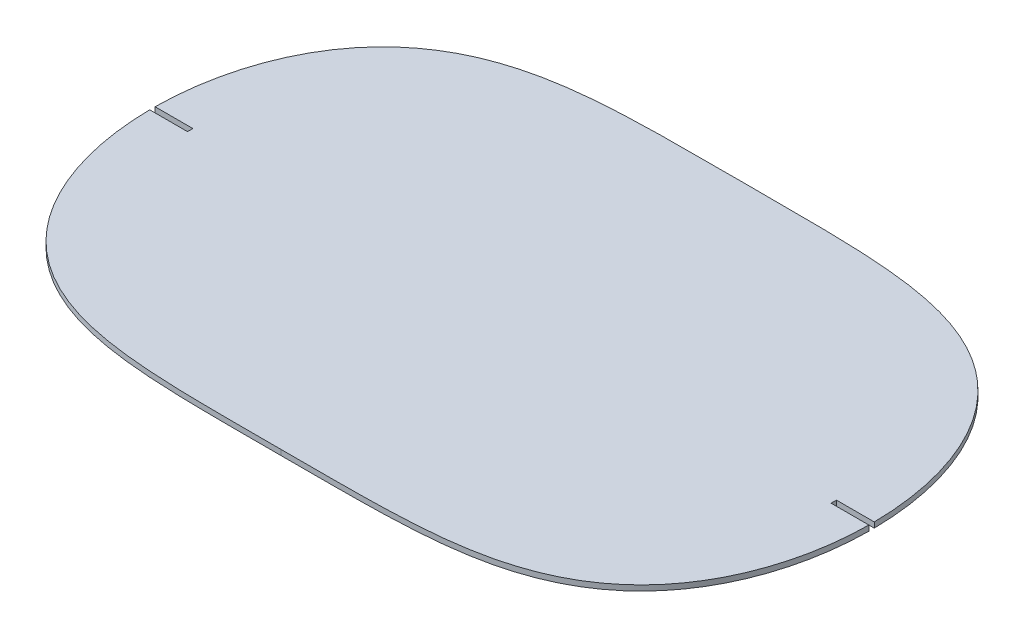
SolidWorks part; units mm, degrees
ref_plane "Front Plane" through (0, 0, 0) normal (0, 0, 1) x (1, 0, 0)
ref_plane "Top Plane" through (0, 0, 0) normal (0, 1, 0) x (1, 0, 0)
ref_plane "Right Plane" through (0, 0, 0) normal (1, 0, 0) x (0, 0, -1)
sketch "Sketch1" plane through (0, 0, 0) normal (0, 1, 0) x (1, 0, 0)
  spline S0 degree 4 poles (0, 129.0994) (4.3298, 129.0999) (12.9895, 129.0995) (25.9763, 129.0992) (43.2902, 129.014) (60.6007, 128.6712) (77.8947, 127.8129) (95.543, 126.046) (113.014, 122.896) (130.0464, 117.7971) (146.1581, 110.2269) (160.4313, 100.265) (172.6933, 87.9119) (182.6634, 73.6634) (190.3404, 58.0791) (195.8654, 41.6227) (199.4008, 24.6362) (201.0699, 7.3707) (200.9352, -9.9735) (198.9912, -27.2107) (195.1663, -44.1354) (189.3287, -60.4854) (181.3147, -75.9018) (170.9944, -89.9023) (157.8662, -102.4377) (141.9679, -112.6829) (124.642, -119.7567) (106.7084, -124.2192) (88.4462, -126.9034) (70.0513, -128.3227) (45.6298, -129.0998) (25.3491, -129.0993) (10.1399, -129.0994) (0, -129.0994) knots 0 0 0 0 0 0.03122 0.06244 0.093642 0.124843 0.156053 0.187263 0.221451 0.252662 0.283872 0.315082 0.346292 0.377502 0.408713 0.439923 0.471133 0.502344 0.533554 0.564765 0.595975 0.627185 0.658396 0.689606 0.720816 0.757371 0.793926 0.823852 0.853778 0.890332 0.926886 1 1 1 1 1 construction
  spline S1 degree 4 poles (0, 129.0994) (4.3298, 129.0999) (12.9895, 129.0995) (25.9763, 129.0992) (43.2902, 129.014) (60.6007, 128.6712) (77.8947, 127.8129) (95.543, 126.046) (113.014, 122.896) (130.0464, 117.7971) (146.1581, 110.2269) (160.4313, 100.265) (172.6933, 87.9119) (182.6634, 73.6634) (190.3404, 58.0791) (195.8654, 41.6227) (199.4008, 24.6362) (201.0699, 7.3707) (200.9352, -9.9735) (198.9912, -27.2107) (195.1663, -44.1354) (189.3287, -60.4854) (181.3147, -75.9018) (170.9944, -89.9023) (157.8662, -102.4377) (141.9679, -112.6829) (124.642, -119.7567) (106.7084, -124.2192) (88.4462, -126.9034) (70.0513, -128.3227) (45.6298, -129.0998) (25.3491, -129.0993) (10.1399, -129.0994) (0, -129.0994) knots 0 0 0 0 0 0.03122 0.06244 0.093642 0.124843 0.156053 0.187263 0.221451 0.252662 0.283872 0.315082 0.346292 0.377502 0.408713 0.439923 0.471133 0.502344 0.533554 0.564765 0.595975 0.627185 0.658396 0.689606 0.720816 0.757371 0.793926 0.823852 0.853778 0.890332 0.926886 1 1 1 1 1
  spline S2 degree 4 poles (0, 129.0994) (-4.3298, 129.0999) (-12.9895, 129.0995) (-25.9763, 129.0992) (-43.2902, 129.014) (-60.6007, 128.6712) (-77.8947, 127.8129) (-95.543, 126.046) (-113.014, 122.896) (-130.0464, 117.7971) (-146.1581, 110.2269) (-160.4313, 100.265) (-172.6933, 87.9119) (-182.6634, 73.6634) (-190.3404, 58.0791) (-195.8654, 41.6227) (-199.4008, 24.6362) (-201.07, 7.3707) (-200.9352, -9.9735) (-198.9912, -27.2107) (-195.1663, -44.1354) (-189.3287, -60.4854) (-181.3147, -75.9018) (-170.9944, -89.9023) (-157.8662, -102.4377) (-141.9679, -112.6829) (-124.642, -119.7567) (-106.7084, -124.2192) (-88.4462, -126.9034) (-70.0513, -128.3227) (-45.6298, -129.0998) (-25.3491, -129.0993) (-10.1399, -129.0994) (0, -129.0994) knots 0 0 0 0 0 0.03122 0.06244 0.093642 0.124843 0.156053 0.187263 0.221451 0.252662 0.283872 0.315082 0.346292 0.377502 0.408713 0.439923 0.471133 0.502344 0.533554 0.564765 0.595975 0.627185 0.658396 0.689606 0.720816 0.757371 0.793926 0.823852 0.853778 0.890332 0.926886 1 1 1 1 1 construction
  spline S3 degree 4 poles (0, 129.0994) (-4.3298, 129.0999) (-12.9895, 129.0995) (-25.9763, 129.0992) (-43.2902, 129.014) (-60.6007, 128.6712) (-77.8947, 127.8129) (-95.543, 126.046) (-113.014, 122.896) (-130.0464, 117.7971) (-146.1581, 110.2269) (-160.4313, 100.265) (-172.6933, 87.9119) (-182.6634, 73.6634) (-190.3404, 58.0791) (-195.8654, 41.6227) (-199.4008, 24.6362) (-201.07, 7.3707) (-200.9352, -9.9735) (-198.9912, -27.2107) (-195.1663, -44.1354) (-189.3287, -60.4854) (-181.3147, -75.9018) (-170.9944, -89.9023) (-157.8662, -102.4377) (-141.9679, -112.6829) (-124.642, -119.7567) (-106.7084, -124.2192) (-88.4462, -126.9034) (-70.0513, -128.3227) (-45.6298, -129.0998) (-25.3491, -129.0993) (-10.1399, -129.0994) (0, -129.0994) knots 0 0 0 0 0 0.03122 0.06244 0.093642 0.124843 0.156053 0.187263 0.221451 0.252662 0.283872 0.315082 0.346292 0.377502 0.408713 0.439923 0.471133 0.502344 0.533554 0.564765 0.595975 0.627185 0.658396 0.689606 0.720816 0.757371 0.793926 0.823852 0.853778 0.890332 0.926886 1 1 1 1 1
extrude "Boss-Extrude2" add sketch "Sketch1" along normal blind 3 contours S1 S3
sketch "Sketch2" plane through (0, 0, 0) normal (0, 1, 0) x (1, 0, 0)
sketch "Sketch4" plane through (0, 0, 0) normal (0, 1, 0) x (1, 0, 0)
  line L4 (-179.7305, 1.5) -> (-203.6748, 1.5)
  line L5 (-179.7305, 1.5) -> (-179.7305, -1.5)
  line L6 (-179.7305, -1.5) -> (-203.6748, -1.5)
  line L7 (-203.6748, 1.5) -> (-203.6748, -1.5)
  point P0 (0, 0)
extrude "Cut-Extrude2" cut sketch "Sketch4" along normal blind 98
sketch "Sketch5" plane through (0, 0, 0) normal (0, 1, 0) x (1, 0, 0)
  line L4 (179.7305, 1.5) -> (207.0637, 1.5)
  line L5 (179.7305, 1.5) -> (179.7305, -1.5)
  line L6 (179.7305, -1.5) -> (207.0637, -1.5)
  line L7 (207.0637, 1.5) -> (207.0637, -1.5)
extrude "Cut-Extrude3" cut sketch "Sketch5" along normal blind 39
